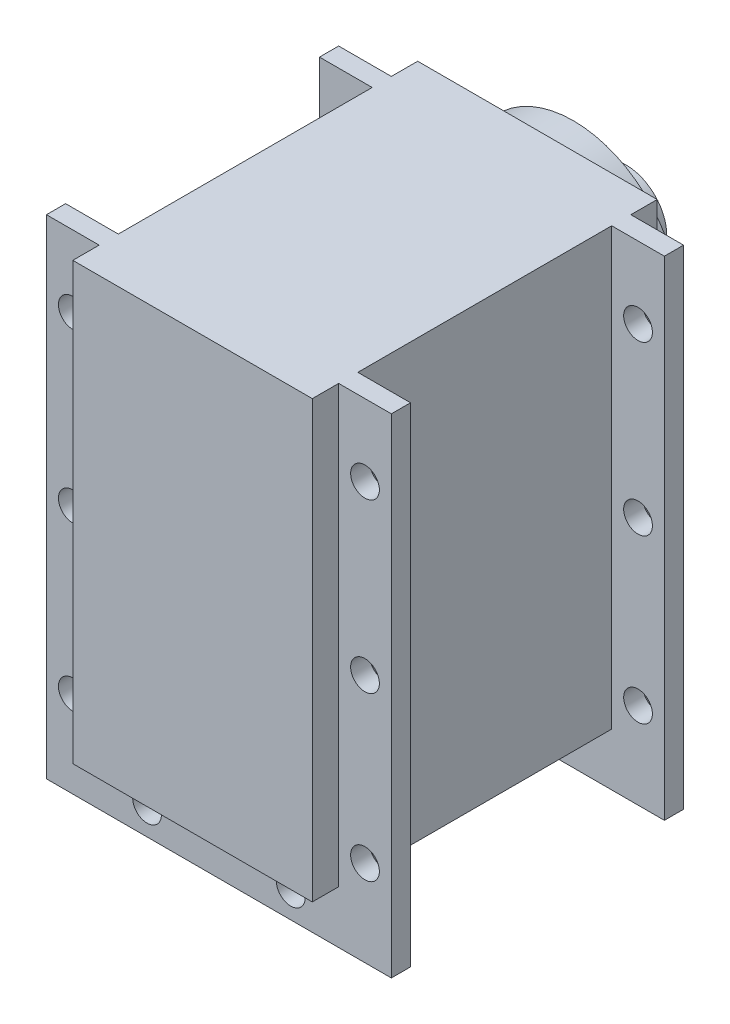
SolidWorks part; units mm, degrees
ref_plane "Front Plane" through (0, 0, 0) normal (0, 0, 1) x (1, 0, 0)
ref_plane "Top Plane" through (0, 0, 0) normal (0, 1, 0) x (1, 0, 0)
ref_plane "Right Plane" through (0, 0, 0) normal (1, 0, 0) x (0, 0, -1)
sketch "Sketch1" plane through (0, 0, 0) normal (0, 0, 1) x (1, 0, 0)
  line L1 (-12.5, -22.75) -> (12.5, -22.75)
  line L2 (-12.5, -22.75) -> (-12.5, 22.75)
  line L3 (-12.5, 22.75) -> (12.5, 22.75)
  line L4 (12.5, -22.75) -> (12.5, 22.75)
  line L5 (-12.5, -22.75) -> (12.5, 22.75) construction
  line L6 (-12.5, 22.75) -> (12.5, -22.75) construction
  point P0 (0, 0)
  dimension "D1" = 25
  dimension "D2" = 45.5
extrude "Boss-Extrude1" add sketch "Sketch1" along normal blind 36
sketch "Sketch2" plane through (0, 0, 0) normal (0, 0, -1) x (-1, 0, 0)
  line L0 (-12.5, 22.75) -> (12.5, 22.75) construction
  line L1 (-18, 22.75) -> (18, 22.75)
  line L2 (-18, 22.75) -> (-18, -28.25)
  line L3 (-18, -28.25) -> (18, -28.25)
  line L4 (18, 22.75) -> (18, -28.25)
  line L5 (-12.5, -22.75) -> (-12.5, 22.75) construction
  line L6 (12.5, 22.75) -> (12.5, -22.75) construction
  line L7 (12.5, -22.75) -> (-12.5, -22.75) construction
  line L8 (-18, 20.9329) -> (-12.5, 20.9329) construction
  line L9 (12.5, 18.8932) -> (18, 18.8932) construction
  line L10 (2.0803, -28.25) -> (2.0803, -22.75) construction
  circle A0 centre (-15.25, 15.25) radius 1.5
  circle A1 centre (-15.25, -2.25) radius 1.5
  circle A2 centre (-15.25, -19.25) radius 1.5
  circle A3 centre (-7.5, -25.5) radius 1.5
  circle A4 centre (7.5, -25.5) radius 1.5
  circle A5 centre (15.25, -19.25) radius 1.5
  circle A6 centre (15.25, -2.25) radius 1.5
  circle A7 centre (15.25, 15.25) radius 1.5
  point P28 (2.0803, -25.5)
  point P29 (-15.25, 20.9329)
  point P32 (15.25, 18.8932)
  dimension "D4" = 3
  dimension "D5" = 7.5
  dimension "D1" = 5.5
  dimension "D2" = 5.5
  dimension "D3" = 5.5
  dimension "D6" = 25
  dimension "D7" = 42
  dimension "D8" = 5
  dimension "D9" = 5
extrude "Boss-Extrude2" add sketch "Sketch2" against normal blind 2 from offset 2.75 offset against normal yes
sketch "Sketch3" plane through (0, 0, 0) normal (0, 0, -1) x (-1, 0, 0)
  line L0 (-12.5, 22.75) -> (12.5, 22.75) construction
  circle A0 centre (0, 10.75) radius 11
  point P5 (0, 22.75)
  dimension "D1" = 22
  dimension "D2" = 12
extrude "Boss-Extrude3" add sketch "Sketch3" along normal blind 3.75
sketch "Sketch4" plane through (0, 0, -3.75) normal (0, 0, -1) x (-1, 0, 0)
  circle A0 centre (0, 18.75) radius 1.5
  circle A1 centre (0, 10.75) radius 11 construction
  circle A2 centre (-5.6569, 16.4069) radius 1.5
  circle A3 centre (-8, 10.75) radius 1.5
  circle A4 centre (-5.6569, 5.0931) radius 1.5
  circle A5 centre (0, 2.75) radius 1.5
  circle A6 centre (5.6569, 5.0931) radius 1.5
  circle A7 centre (8, 10.75) radius 1.5
  circle A8 centre (5.6569, 16.4069) radius 1.5
  point P21 (0, 10.75)
  dimension "D1" = 3
  dimension "D2" = 8
  dimension "D3" = 8
extrude "Cut-Extrude1" cut sketch "Sketch4" against normal blind 3.75
sketch "Sketch5" plane through (0, 0, -3.75) normal (0, 0, -1) x (-1, 0, 0)
  circle A0 centre (0, 10.75) radius 4.25
  dimension "D1" = 8.5
extrude "Boss-Extrude4" add sketch "Sketch5" along normal blind 5.5
sketch "Sketch6" plane through (0, 0, 36) normal (0, 0, 1) x (1, 0, 0)
  line L1 (-18, 22.75) -> (18, 22.75)
  line L2 (-18, 22.75) -> (-18, -28.25)
  line L3 (-18, -28.25) -> (18, -28.25)
  line L4 (18, 22.75) -> (18, -28.25)
  line L8 (-18, 20.9329) -> (-12.5, 20.9329) construction
  line L9 (12.5, 18.8932) -> (18, 18.8932) construction
  line L10 (2.0803, -28.25) -> (2.0803, -22.75) construction
  circle A0 centre (-15.25, 15.25) radius 1.5
  circle A1 centre (-15.25, -2.25) radius 1.5
  circle A2 centre (-15.25, -19.25) radius 1.5
  circle A3 centre (-7.5, -25.5) radius 1.5
  circle A4 centre (7.5, -25.5) radius 1.5
  circle A5 centre (15.25, -19.25) radius 1.5
  circle A6 centre (15.25, -2.25) radius 1.5
  circle A7 centre (15.25, 15.25) radius 1.5
  point P28 (2.0803, -25.5)
  point P29 (-15.25, 20.9329)
  point P32 (15.25, 18.8932)
  dimension "D4" = 3
  dimension "D5" = 7.5
  dimension "D1" = 36
  dimension "D6" = 25
  dimension "D7" = 42
extrude "Boss-Extrude5" add sketch "Sketch6" against normal blind 2 from offset 2.75
